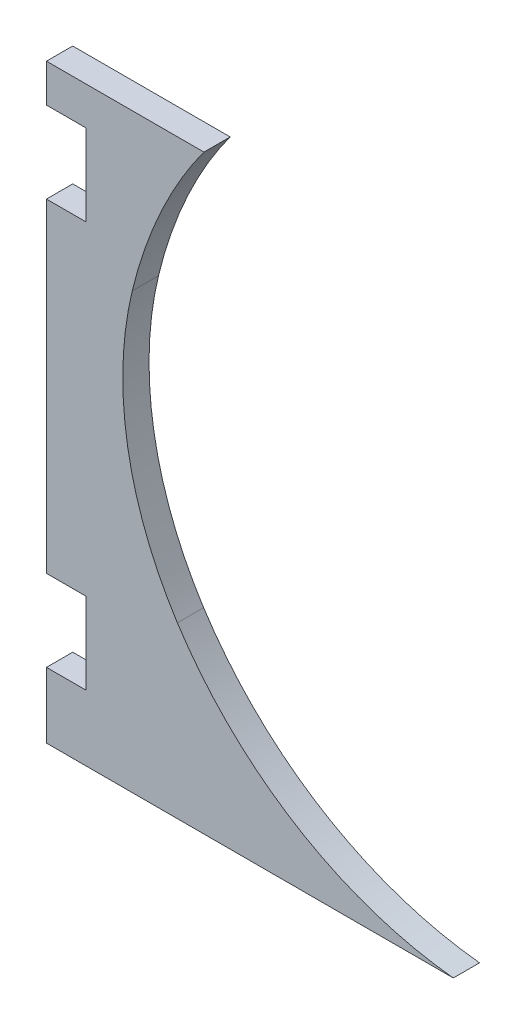
SolidWorks part; units mm, degrees
ref_plane "Front Plane" through (0, 0, 0) normal (0, 0, 1) x (1, 0, 0)
ref_plane "Top Plane" through (0, 0, 0) normal (0, 1, 0) x (1, 0, 0)
ref_plane "Right Plane" through (0, 0, 0) normal (1, 0, 0) x (0, 0, -1)
sketch "Sketch1" plane through (0, 0, 0) normal (0, 0, 1) x (1, 0, 0)
  line L1 (-70, 112.5) -> (70, 112.5)
  line L2 (-70, 112.5) -> (-70, -112.5)
  line L3 (-70, -112.5) -> (70, -112.5)
  line L4 (70, 112.5) -> (70, -112.5)
  line L5 (-70, 112.5) -> (70, -112.5) construction
  line L6 (-70, -112.5) -> (70, 112.5) construction
  point P0 (0, 0)
  dimension "D1" = 140
  dimension "D2" = 225
extrude "Boss-Extrude1" add sketch "Sketch1" along normal blind 10
sketch "Sketch2" plane through (0, 0, 10) normal (0, 0, 1) x (1, 0, 0)
  line L0 (-70, -112.5) -> (70, -112.5) construction
  line L1 (-70, 112.5) -> (-70, -112.5) construction
  line L3 (-35, 112.5) -> (70, 112.5)
  line L4 (70, 112.5) -> (70, -112.5)
  line L5 (70, 112.5) -> (-70, 112.5) construction
  arc A0 (70, -112.5) -> (-57, 12.8292) centre (85, 29.7111) cw
  spline S1 degree 3 poles (-57, 12.8292) (-57.2309, 51.9086) (-43.4996, 87.4349) (-25, 112.5) knots 0 0 0 0 1 1 1 1
  spline S2 degree 1 poles (-57, 12.8292) (70, -112.5) knots 0 0 1 1
  line M1 (70, -112.5) -> (70, 112.5)
  line M2 (70, 112.5) -> (-70, 112.5)
  dimension "D1" = 143
  dimension "D8" = 45
  dimension "D2" = 13
  dimension "D4" = 225
  dimension "D5" = 15
  dimension "D6" = 142.2111
extrude "Cut-Extrude1" cut sketch "Sketch2" against normal blind 10 contours S1 S2 M1 M2 | S2 A0
fillet "Fillet1" radius 130 1 edges at (-57, 12.8292, 5)
sketch "Sketch3" plane through (-70, 0, 0) normal (-1, 0, 0) x (0, 0, 1)
  line L1 (0, 112.5) -> (10, 112.5)
  line L2 (0, 112.5) -> (0, -112.5)
  line L3 (0, -112.5) -> (10, -112.5)
  line L4 (10, 112.5) -> (10, -112.5)
extrude "Boss-Extrude2" add sketch "Sketch3" along normal blind 15
sketch "Sketch4" plane through (0, 0, 0) normal (0, 0, -1) x (-1, 0, 0)
  line L0 (85, 112.5) -> (85, -112.5) construction
  line L1 (85, 98) -> (70, 98)
  line L2 (85, 98) -> (85, 67)
  line L3 (85, 67) -> (70, 67)
  line L4 (70, 98) -> (70, 67)
  line L5 (85, -112.5) -> (-70, -112.5) construction
  line L6 (85, -87.5) -> (70, -87.5)
  line L7 (85, -87.5) -> (85, -56.5)
  line L8 (85, -56.5) -> (70, -56.5)
  line L9 (70, -87.5) -> (70, -56.5)
  line L11 (25, 112.5) -> (85, 112.5) construction
  point P10 (77.5, -56.5)
  point P14 (85, 82.5)
  dimension "D1" = 31
  dimension "D2" = 15
  dimension "D3" = 31
  dimension "D4" = 15
  dimension "D5" = 25
  dimension "D6" = 30
extrude "Cut-Extrude3" cut sketch "Sketch4" against normal through all
